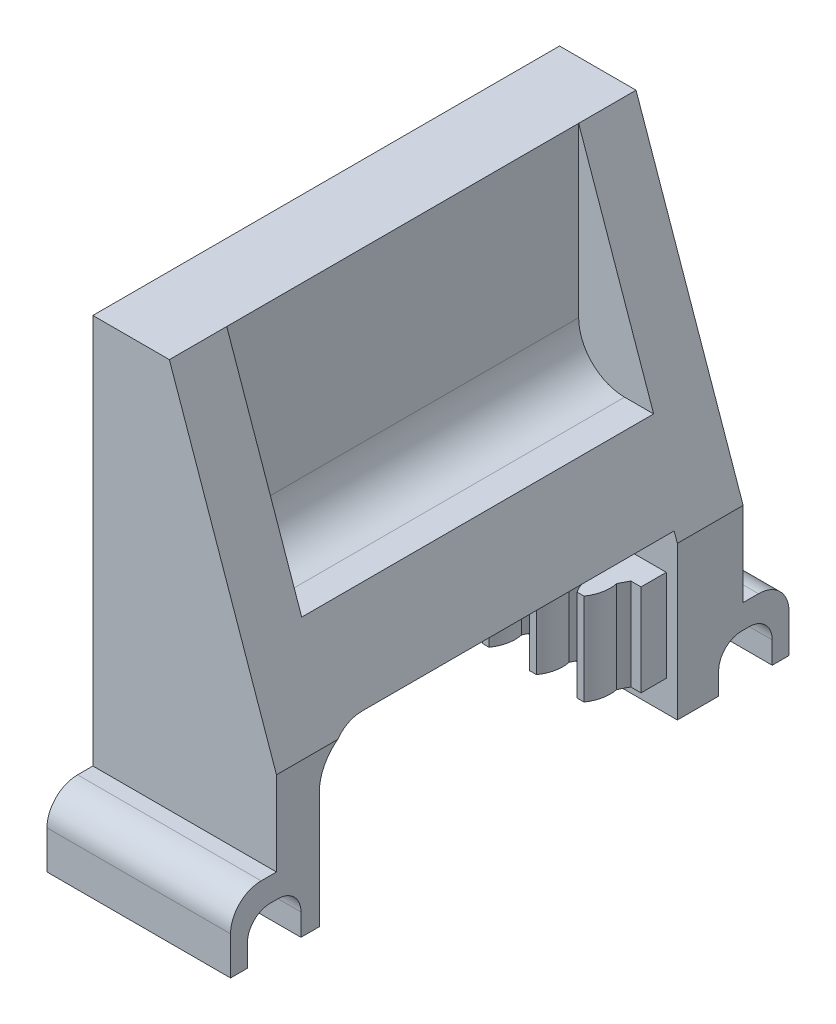
SolidWorks part; units mm, degrees
ref_plane "Front Plane" through (0, 0, 0) normal (0, 0, 1) x (1, 0, 0)
ref_plane "Top Plane" through (0, 0, 0) normal (0, 1, 0) x (1, 0, 0)
ref_plane "Right Plane" through (0, 0, 0) normal (1, 0, 0) x (0, 0, -1)
sketch "Sketch1" plane through (0, 0, 0) normal (0, 0, 1) x (1, 0, 0)
  line L0 (0, 0) -> (0, -30)
  line L1 (0, -30) -> (12, -30)
  line L2 (12, -30) -> (12, -20)
  line L3 (12, -20) -> (5, 0)
  line L4 (5, 0) -> (0, 0)
  dimension "D1" = 30
  dimension "D2" = 12
  dimension "D3" = 10
  dimension "D4" = 5
extrude "Boss-Extrude1" add sketch "Sketch1" against normal blind 30.5
sketch "Sketch4" plane through (0, 0, 0) normal (-1, 0, 0) x (0, 0, 1)
  line L0 (-30.5, 0) -> (-30.5, -30) construction
  line L1 (-26.2, -19.3999) -> (-2.8, -19.3999)
  line L2 (-26.2, -19.3999) -> (-26.2, -32.3999)
  line L3 (-26.2, -32.3999) -> (-2.8, -32.3999)
  line L4 (-2.8, -19.3999) -> (-2.8, -32.3999)
  point P4 (-26.2, -25.8999)
  dimension "D1" = 23.4
  dimension "D2" = 13
  dimension "D3" = 4.3
extrude "Cut-Extrude2" cut sketch "Sketch4" against normal blind 25 contours L2 L1 L4 L3
ref_plane "Plane1" through (0, 0, -15.25) normal (0, 0, 1) x (1, 0, 0)
sketch "Sketch6" plane through (0, 0, -15.25) normal (0, 0, 1) x (1, 0, 0)
  line L0 (5, 0) -> (5, -14)
  line L1 (5, -14) -> (9.9, -14)
  line L2 (12, -20) -> (5, 0) construction
  line L3 (9.9, -14) -> (5, 0)
  dimension "D1" = 14
extrude "Cut-Extrude4" cut sketch "Sketch6" against normal mid plane 23
ref_plane "Plane2" through (0, -26.4, 0) normal (0, 1, 0) x (1, 0, 0)
ref_plane "Plane3" through (0, -28, 0) normal (0, 1, 0) x (1, 0, 0)
sketch "Sketch7" plane through (0, -28, 0) normal (0, 1, 0) x (1, 0, 0)
  line L0 (11.2768, 26.25) -> (-19.7232, 26.25)
  line L62 (-6.6, 15.25) -> (6.6, 15.25) construction
  line L162 (11.2768, 26.25) -> (11.2768, 24.55)
  line L172 (-19.7232, 24.55) -> (-19.7232, 26.25)
  line L243 (11.2768, 24.55) -> (-19.7232, 24.55)
  dimension "D2" = 31
  dimension "D3" = 1.7
  dimension "D7" = 11
extrude "Boss-Extrude3" add sketch "Sketch7" along normal blind 6
sketch "Sketch10" plane through (0, -28, 0) normal (0, 1, 0) x (1, 0, 0)
  line L1 (9.7091, 22.1637) -> (9.7091, 23.4692) construction
  line L2 (9.9303, 22.1637) -> (9.488, 22.1637)
  line L4 (-19.7232, 24.55) -> (11.2768, 24.55) construction
  line L5 (8.8091, 24.55) -> (10.6091, 24.55)
  arc A0 (9.9303, 22.1637) -> (10.2974, 23.9324) centre (8.0599, 23.4744) ccw
  arc A1 (10.2974, 23.9324) -> (10.6091, 24.55) centre (18.9801, 19.9379) cw
  arc A2 (9.1208, 23.9324) -> (8.8091, 24.55) centre (0.4382, 19.9379) ccw
  arc A3 (9.488, 22.1637) -> (9.1208, 23.9324) centre (11.3584, 23.4744) cw
  point P7 (0, 0)
  point P15 (9.6229, 21.3818)
  point P16 (9.1381, 23.4692)
  point P17 (8.8091, 24.55)
  point P18 (10.2737, 21.6365)
  point P19 (9.1868, 23.4692)
  point P20 (9.6348, 22.1637)
  point P21 (9.2088, 23.7354)
  dimension "D1" = 1.8
extrude "Boss-Extrude4" add sketch "Sketch10" along normal blind 6
pattern_linear "LPattern1" count 10 spacing 3.1 along (-1, 0, 0) of "Boss-Extrude4"
sketch "Sketch11" plane through (0, 0, -30.5) normal (0, 0, -1) x (-1, 0, 0)
  line L0 (-12, -30) -> (-12, -20) construction
  line L1 (-12, -25.5) -> (0, -25.5)
  line L2 (-12, -25.5) -> (-12, -30)
  line L3 (-12, -30) -> (0, -30)
  line L4 (0, -25.5) -> (0, -30)
  dimension "D1" = 4.5
extrude "Boss-Extrude5" add sketch "Sketch11" along normal blind 3
fillet "Fillet1" radius 2 1 edges at (6, -25.5, -33.5)
mirror "Mirror1" about plane through (0, 0, -15.25) normal (0, 0, 1) of "Boss-Extrude5"
fillet "Fillet2" radius 2 1 edges at (6, -25.5, 3)
fillet "Fillet5" radius 3 2 edges at (5, -14, -15.25) (5.895, -19.3999, -2.8)
sketch "Sketch12" plane through (0, 0, 0) normal (-1, 0, 0) x (0, 0, 1)
  line L0 (-15.25, -20.6354) -> (-15.25, -36.9741) construction
  line L1 (-32.4, -27.0644) -> (-28.9, -27.0644)
  line L2 (-32.4, -27.0644) -> (-32.4, -30.5644)
  line L3 (-32.4, -30.5644) -> (-28.9, -30.5644)
  line L4 (-28.9, -27.0644) -> (-28.9, -30.5644)
  line L5 (-2.8, -30) -> (-2.8, -22.3999) construction
  line L11 (-15.25, -16.5) -> (-15.25, 16.5) construction
  line L12 (1.9, -30.5644) -> (-1.6, -30.5644)
  line L13 (-1.6, -27.0644) -> (-1.6, -30.5644)
  line L14 (1.9, -27.0644) -> (-1.6, -27.0644)
  line L15 (1.9, -27.0644) -> (1.9, -30.5644)
  dimension "D1" = 3.5
  dimension "D2" = 3.5
  dimension "D3" = 1.2
extrude "Cut-Extrude5" cut sketch "Sketch12" against normal up to surface (12 mm away) up to face at (12, -25.043, -0.2378)
fillet "Fillet6" radius 1.5 4 edges at (6, -27.0644, -32.4) (6, -27.0644, -28.9) (6, -27.0644, 1.9) (6, -27.0644, -1.6)
